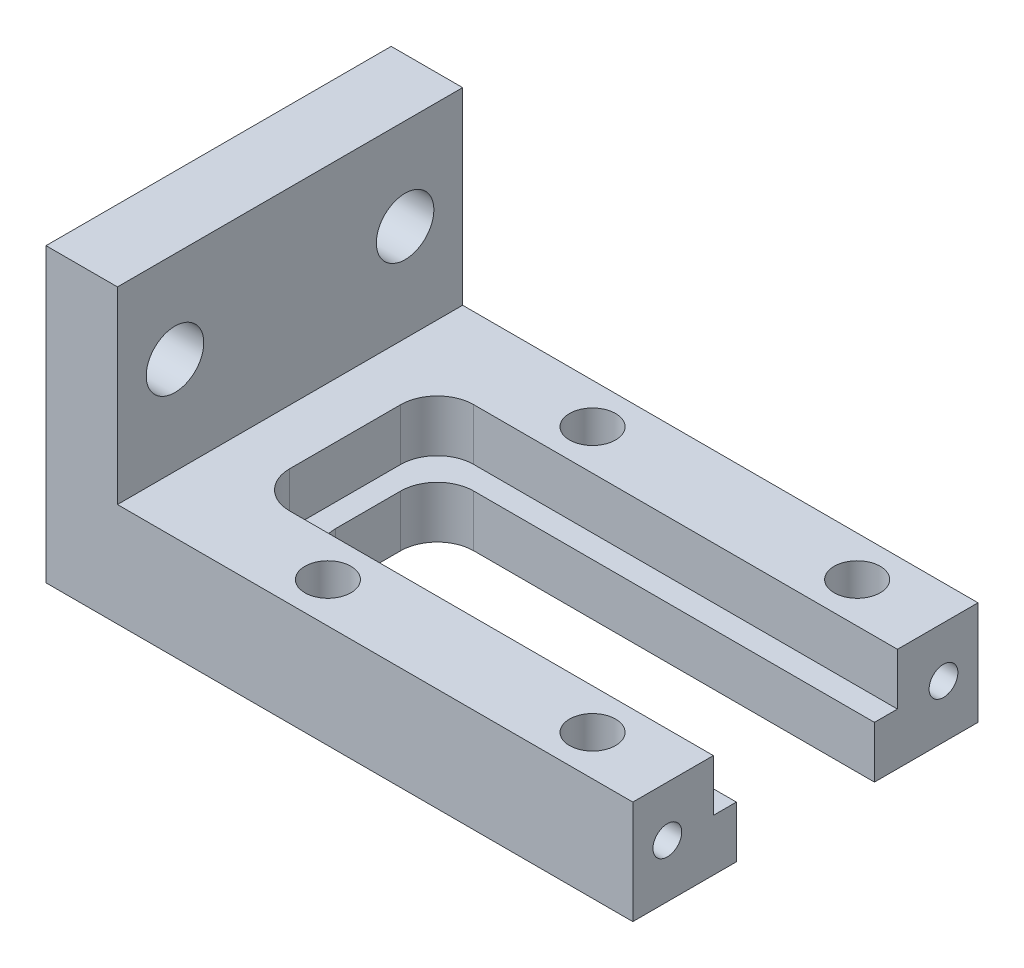
SolidWorks part; units mm, degrees
ref_plane "Front Plane" through (0, 0, 0) normal (0, 0, 1) x (1, 0, 0)
ref_plane "Top Plane" through (0, 0, 0) normal (0, 1, 0) x (1, 0, 0)
ref_plane "Right Plane" through (0, 0, 0) normal (1, 0, 0) x (0, 0, -1)
sketch "Sketch1" plane through (0, 0, 0) normal (0, 1, 0) x (1, 0, 0)
  line L1 (-25.5, -15) -> (25.5, -15)
  line L2 (-25.5, -15) -> (-25.5, 15)
  line L3 (-25.5, 15) -> (25.5, 15)
  line L4 (25.5, -15) -> (25.5, 15)
  line L5 (-25.5, -15) -> (25.5, 15) construction
  line L6 (-25.5, 15) -> (25.5, -15) construction
  point P0 (0, 0)
  dimension "D1" = 30
  dimension "D2" = 51
extrude "Boss-Extrude1" add sketch "Sketch1" along normal blind 9
sketch "Sketch2" plane through (0, 9, 0) normal (0, 1, 0) x (1, 0, 0)
  line L0 (25.5, 15) -> (-25.5, 15) construction
  line L1 (-25.5, -15) -> (-19.29, -15)
  line L2 (-25.5, -15) -> (-25.5, 15)
  line L3 (-25.5, 15) -> (-19.29, 15)
  line L4 (-19.29, -15) -> (-19.29, 15)
  dimension "D1" = 6.21
extrude "Boss-Extrude2" add sketch "Sketch2" along normal blind 16.38
sketch "Sketch3" plane through (0, 9, 0) normal (0, 1, 0) x (1, 0, 0)
  line L0 (25.5, -15) -> (25.5, 15) construction
  line L1 (25.5, -8) -> (-14.5, -8)
  line L2 (25.5, -8) -> (25.5, 8)
  line L3 (25.5, 8) -> (-14.5, 8)
  line L4 (-14.5, -8) -> (-14.5, 8)
  dimension "D1" = 16
  dimension "D2" = 7
  dimension "D3" = 40
sketch "Sketch4" plane through (0, 9, 0) normal (0, 1, 0) x (1, 0, 0)
  line L0 (-25.5, 15) -> (-25.5, -15) construction
  line L1 (25.5, 15) -> (-19.29, 15) construction
  line L2 (-4.5, -11.5) -> (18.5, -11.5)
  line L3 (-4.5, -11.5) -> (-4.5, 11.5)
  line L4 (-4.5, 11.5) -> (18.5, 11.5)
  line L5 (18.5, -11.5) -> (18.5, 11.5)
  line L6 (-4.5, -11.5) -> (18.5, 11.5) construction
  line L7 (-4.5, 11.5) -> (18.5, -11.5) construction
  circle A0 centre (7, 0) radius 5.0635
  circle A1 centre (7, 0) radius 8
  dimension "D2" = 3.5
  dimension "D1" = 32.5
  dimension "D3" = 3.5
  dimension "D4" = 23
extrude "Cut-Extrude1" cut sketch "Sketch3" against normal blind 4.5
fillet "Fillet1" radius 3.175 2 edges at (-14.5, 6.75, 8) (-14.5, 6.75, -8)
sketch "Sketch5" plane through (0, 4.5, 0) normal (0, 1, 0) x (1, 0, 0)
  line L1 (25.5, -8) -> (25.5, 8) construction
  line L2 (25.5, -6) -> (-9.325, -6)
  line L3 (25.5, -6) -> (25.5, 6)
  line L4 (25.5, 6) -> (-9.325, 6)
  line L5 (-12.5, -2.825) -> (-12.5, 2.825)
  line L7 (-14.5, 4.825) -> (-14.5, -4.825) construction
  arc A0 (-9.325, -6) -> (-12.5, -2.825) centre (-9.325, -2.825) cw
  arc A1 (-9.325, 6) -> (-12.5, 2.825) centre (-9.325, 2.825) ccw
  point P6 (-14.5, 0)
  dimension "D4" = 3.175
  dimension "D1" = 12
  dimension "D2" = 2
  dimension "D3" = 2
extrude "Cut-Extrude2" cut sketch "Sketch5" against normal through all
sketch "Sketch6" plane through (-19.29, 0, 0) normal (1, 0, 0) x (0, 0, -1)
  line L0 (-15, 25.38) -> (-15, 9) construction
  line L1 (15, 25.38) -> (15, 9) construction
  point P0 (-10, 17.4321)
  point P1 (10, 17.4321)
  dimension "D1" = 5
  dimension "D2" = 5
hole_wizard "Ø5.0 (5) Diameter Hole1" positions "Sketch8" profile "Sketch7" hole size "Ø5.0" standard "ANSI Metric"
sketch "Sketch8" plane through (-19.29, 0, 0) normal (1, 0, 0) x (0, 0, -1)
  point P0 (-10, 17.4321)
  point P3 (10, 17.4321)
sketch "Sketch7" plane through (-19.29, 17.4321, 10) normal (0, 1, 0) x (0, 0, -1)
  line L0 (0, 0) -> (0, 11.5022)
  line L1 (0, 11.5022) -> (2.5, 10)
  line L2 (2.5, 10) -> (2.5, 0)
  line L5 (2.5, 0) -> (0, 0)
  line L10 (0, 11.5022) -> (-2.5, 10) construction
  line L11 (0, -6.35) -> (0, 107.95) construction
  dimension "Hole Dia." = 5
  dimension "Hole Depth" = 10
  dimension "Drill Angle" = 118
hole_wizard "Ø4.0 (4) Diameter Hole1" positions "Sketch10" profile "Sketch9" hole size "Ø4.0" standard "ANSI Metric"
sketch "Sketch10" plane through (0, 9, 0) normal (0, 1, 0) x (1, 0, 0)
  point P0 (73.5795, -261.2664)
  point P2 (-4.5, -11.5)
  point P5 (18.5, -11.5)
  point P8 (18.5, 11.5)
  point P11 (-4.5, 11.5)
sketch "Sketch9" plane through (73.5795, 9, 261.2664) normal (1, 0, 0) x (0, 0, 1)
  line L0 (0, 0) -> (0, 11.2017)
  line L1 (0, 11.2017) -> (2, 10)
  line L2 (2, 10) -> (2, 0)
  line L5 (2, 0) -> (0, 0)
  line L10 (0, 11.2017) -> (-2, 10) construction
  line L11 (0, -6.35) -> (0, 107.95) construction
  dimension "Hole Dia." = 4
  dimension "Hole Depth" = 10
  dimension "Drill Angle" = 118
sketch "Sketch11" plane through (25.5, 0, 0) normal (1, 0, 0) x (0, 0, -1)
  line L0 (-15, 9) -> (-15, 0) construction
  line L1 (15, 9) -> (15, 0) construction
  point P0 (-12, 4.6233)
  point P1 (12, 4.6233)
  dimension "D1" = 3
  dimension "D2" = 3
hole_wizard "M3x0.5 Tapped Hole1" positions "Sketch13" profile "Sketch12" tap size "M3x0.5" standard "ANSI Metric"
sketch "Sketch13" plane through (25.5, 0, 0) normal (1, 0, 0) x (0, 0, -1)
  point P0 (-12, 4.6233)
  point P3 (12, 4.6233)
sketch "Sketch12" plane through (25.5, 4.6233, 12) normal (0, 1, 0) x (0, 0, -1)
  line L0 (0, 0) -> (0, 7.7511)
  line L1 (0, 7.7511) -> (1.25, 7)
  line L2 (1.25, 7) -> (1.25, 0)
  line L5 (1.25, 0) -> (0, 0)
  line L10 (0, 7.7511) -> (-1.25, 7) construction
  line L11 (0, -6.35) -> (0, 107.95) construction
  dimension "Tap Drill Dia." = 2.5
  dimension "Tap Drill Depth" = 7
  dimension "Drill Angle" = 118
cosmetic thread "Hole Thread1" parameters "D1"=6, "D2"=3
cosmetic thread "Hole Thread2" parameters "D1"=6, "D2"=3
